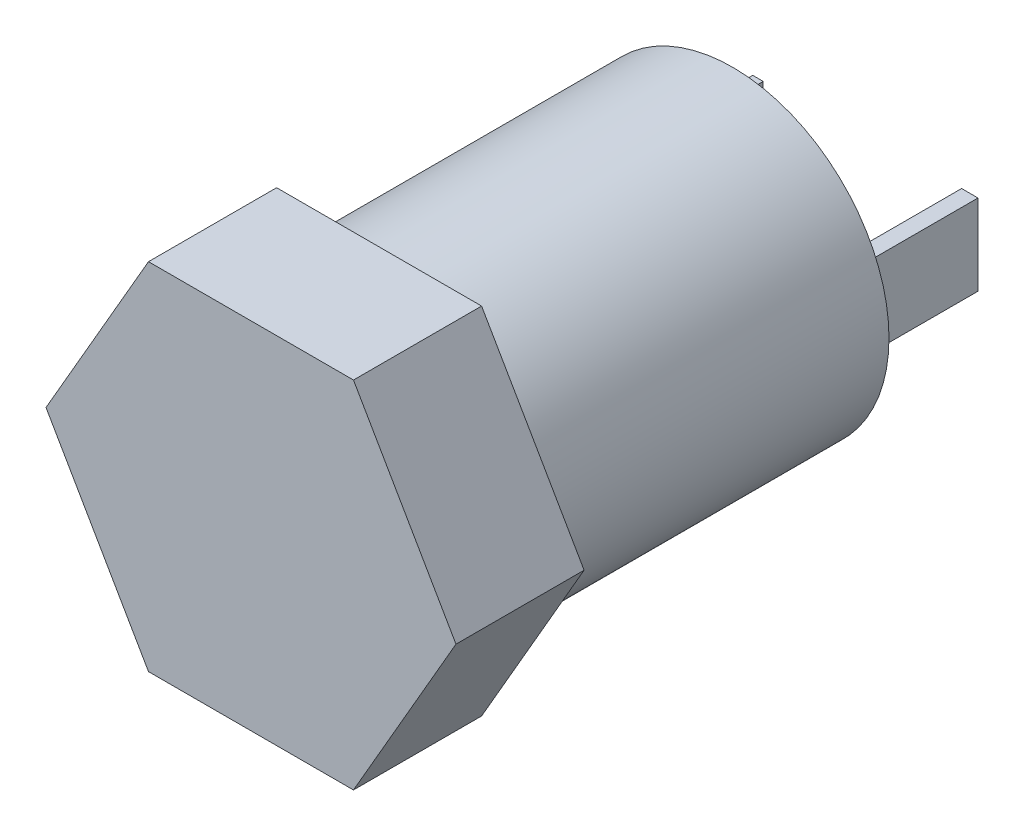
SolidWorks part; units mm, degrees
ref_plane "前视基准面" through (0, 0, 0) normal (0, 0, 1) x (1, 0, 0)
ref_plane "上视基准面" through (0, 0, 0) normal (0, 1, 0) x (1, 0, 0)
ref_plane "右视基准面" through (0, 0, 0) normal (1, 0, 0) x (0, 0, -1)
other "Configuration Table"
sketch "草图1" plane through (0, 0, 0) normal (0, 0, 1) x (1, 0, 0)
  line L0 (0, 0) -> (8, 0) construction
  line L1 (8, 0) -> (4, 6.9282)
  line L2 (4, 6.9282) -> (-4, 6.9282)
  line L3 (-4, 6.9282) -> (-8, 0)
  line L4 (-8, 0) -> (-4, -6.9282)
  line L5 (-4, -6.9282) -> (4, -6.9282)
  line L6 (4, -6.9282) -> (8, 0)
  circle A0 centre (0, 0) radius 6.9282 construction
  dimension "D1" = 16
extrude "凸台-拉伸1" add sketch "草图1" along normal blind 5
sketch "草图2" plane through (0, 0, 0) normal (0, 0, -1) x (-1, 0, 0)
  circle A0 centre (0, 0) radius 6.1
  dimension "D1" = 12.2
extrude "凸台-拉伸2" add sketch "草图2" along normal blind 13.8
sketch "草图3" plane through (0, 0, -13.8) normal (0, 0, -1) x (-1, 0, 0)
  line L1 (-4.3735, 1.2675) -> (-3.7341, 1.2675)
  line L2 (-4.3735, 1.2675) -> (-4.3735, -1.8842)
  line L3 (-4.3735, -1.8842) -> (-3.7341, -1.8842)
  line L4 (-3.7341, 1.2675) -> (-3.7341, -1.8842)
  line L5 (4.0081, 1.0163) -> (4.4192, 1.0163)
  line L6 (4.0081, 1.0163) -> (4.0081, -1.8842)
  line L7 (4.0081, -1.8842) -> (4.4192, -1.8842)
  line L8 (4.4192, 1.0163) -> (4.4192, -1.8842)
extrude "凸台-拉伸3" add sketch "草图3" along normal blind 5.2
